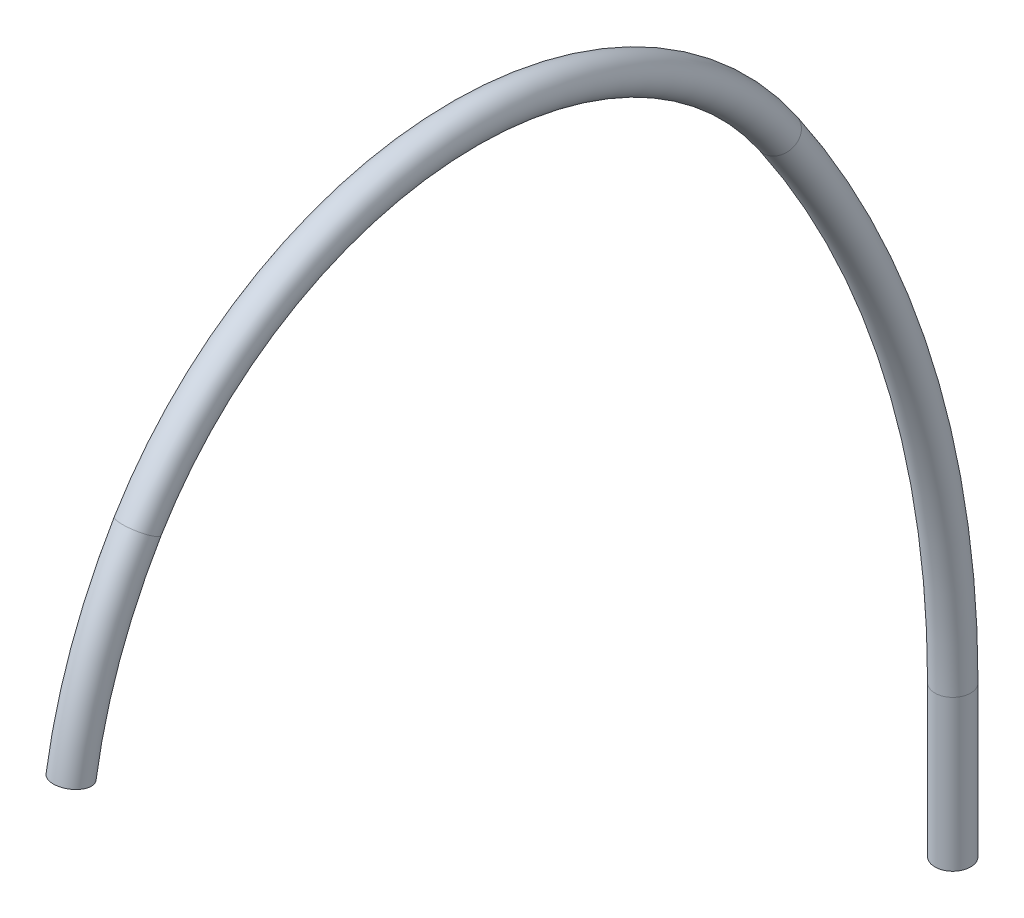
SolidWorks part; units mm, degrees
ref_plane "Alzado" through (0, 0, 0) normal (0, 0, 1) x (1, 0, 0)
ref_plane "Planta" through (0, 0, 0) normal (0, 1, 0) x (1, 0, 0)
ref_plane "Vista lateral" through (0, 0, 0) normal (1, 0, 0) x (0, 0, -1)
sketch "Croquis5" plane through (0, 0, 0) normal (1, 0, 0) x (0, 0, -1)
  line L0 (-12, 40) -> (-12, 82.2054)
  arc A0 (-12, 82.2054) -> (-60.895, 239.966) centre (-290.9561, 82.2054) ccw
  arc A1 (-60.895, 239.966) -> (-240.4284, 234.4298) centre (-148.8864, 179.6274) ccw
  arc A2 (-240.4284, 234.4298) -> (-259.1014, 182.868) centre (-117.1269, 160.6143) ccw
  dimension "D1" = 40
ref_plane "Plano1" through (0, 40, 12) normal (0, 1, 0) x (-1, 0, 0)
sketch "Croquis7" plane through (0, 40, 12) normal (0, 1, 0) x (-1, 0, 0)
  circle A0 centre (0, 0) radius 5
  dimension "D1" = 10
sweep "Barrer1" add profiles "Croquis7" path "Croquis5"
shell "Vaciado2" thickness 1
